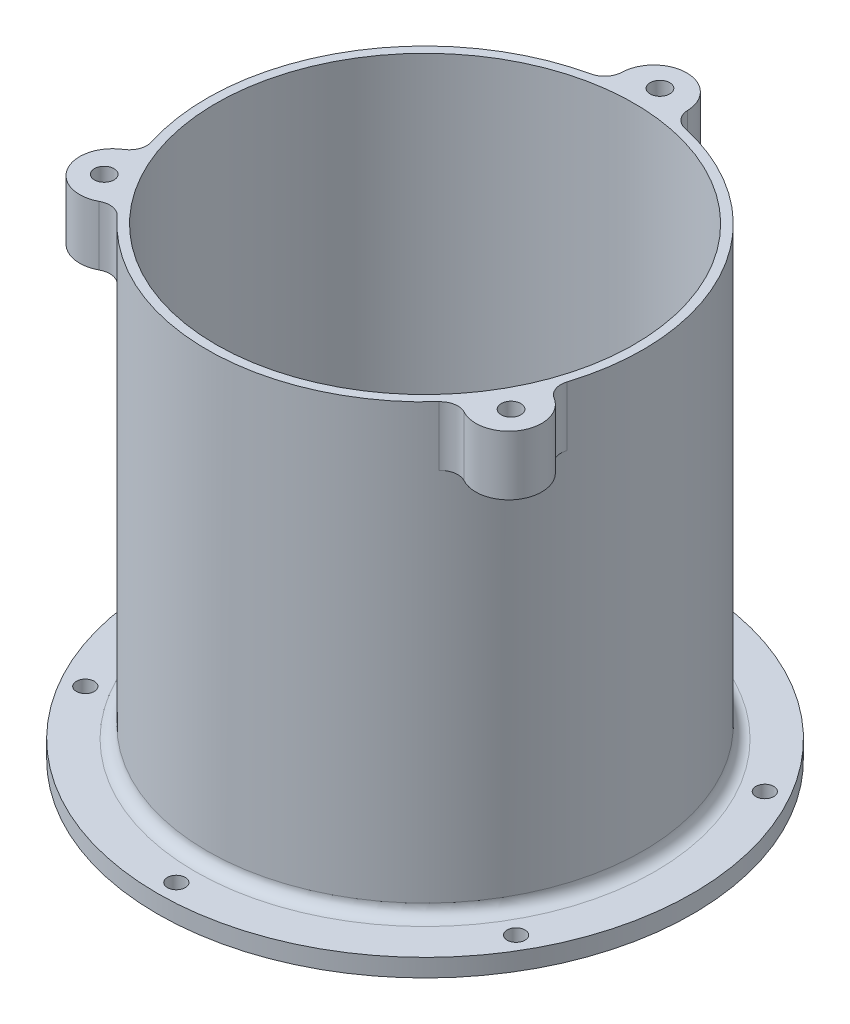
SolidWorks part; units mm, degrees
ref_plane "Front Plane" through (0, 0, 0) normal (0, 0, 1) x (1, 0, 0)
ref_plane "Top Plane" through (0, 0, 0) normal (0, 1, 0) x (1, 0, 0)
ref_plane "Right Plane" through (0, 0, 0) normal (1, 0, 0) x (0, 0, -1)
sketch "Sketch3" plane through (0, 0, 0) normal (0, 1, 0) x (1, 0, 0)
  circle A0 centre (0, 0) radius 45
  circle A1 centre (0, 0) radius 35.15
  dimension "D1" = 70.3
  dimension "D2" = 90
extrude "Boss-Extrude4" add sketch "Sketch3" along normal blind 3
sketch "Sketch4" plane through (0, 3, 0) normal (0, 1, 0) x (1, 0, 0)
  circle A1 centre (0, 0) radius 35.15
  circle A2 centre (0, 0) radius 36.65
  dimension "D1" = 70.3
  dimension "D2" = 73.3
extrude "Boss-Extrude5" add sketch "Sketch4" along normal blind 75
fillet "Fillet1" radius 2 1 edges at (0, 3, 36.65)
sketch "Sketch7" plane through (0, 3, 0) normal (0, 1, 0) x (1, 0, 0)
  line L0 (0, 0) -> (0, 41.825) construction
  circle A1 centre (0, 41.825) radius 1.5
  circle A2 centre (36.2215, 20.9125) radius 1.5
  circle A3 centre (36.2215, -20.9125) radius 1.5
  circle A4 centre (0, -41.825) radius 1.5
  circle A5 centre (-36.2215, -20.9125) radius 1.5
  circle A6 centre (-36.2215, 20.9125) radius 1.5
  point P18 (0, 0)
  dimension "D1" = 41.825
  dimension "D2" = 6
extrude "Cut-Extrude2" cut sketch "Sketch7" against normal through all
sketch "Sketch8" plane through (0, 78, 0) normal (0, 1, 0) x (1, 0, 0)
  line L0 (0, 0) -> (0, 44) construction
  line L1 (0, 0) -> (5.1007, 36.2933) construction
  line L2 (0, 0) -> (-5.1007, 36.2933) construction
  circle A0 centre (0, 0) radius 36.65 construction
  arc A1 (-5.1007, 36.2933) -> (5.1007, 36.2933) centre (0, 0) cw
  arc A3 (33.9813, -13.7293) -> (28.8806, -22.564) centre (31.943, -18.4423) cw
  arc A4 (-28.8806, -22.564) -> (-33.9813, -13.7293) centre (-31.943, -18.4423) cw
  arc A5 (-5.1007, 36.2933) -> (5.1007, 36.2933) centre (0, 38.4638) cw
  arc A6 (33.9813, -13.7293) -> (28.8806, -22.564) centre (33.3107, -19.2319) cw
  arc A7 (33.9813, -13.7293) -> (28.8806, -22.564) centre (0, 0) cw
  arc A8 (-5.1007, 36.2933) -> (5.1007, 36.2933) centre (0, 36.8846) cw
  arc A9 (-28.8806, -22.564) -> (-33.9813, -13.7293) centre (-31.943, -18.4423) cw
  arc A10 (-28.8806, -22.564) -> (-33.9813, -13.7293) centre (-33.3107, -19.2319) cw
  arc A11 (-28.8806, -22.564) -> (-33.9813, -13.7293) centre (0, 0) cw
  arc A12 (33.9813, -13.7293) -> (28.8806, -22.564) centre (31.943, -18.4423) cw
  arc A13 (-5.1007, 36.2933) -> (5.1007, 36.2933) centre (0, 36.8846) cw
  point P19 (0, 0)
  point P37 (0, 0)
  dimension "D1" = 8
  dimension "D2" = 8
  dimension "D3" = 3
extrude "Boss-Extrude7" add sketch "Sketch8" against normal blind 10
sketch "Sketch9" plane through (0, 78, 0) normal (0, 1, 0) x (1, 0, 0)
  line L0 (0, 0) -> (0, 39.5) construction
  circle A0 centre (0, 39.5) radius 1.65
  circle A1 centre (34.208, -19.75) radius 1.65
  circle A2 centre (-34.208, -19.75) radius 1.65
  point P11 (0, 0)
  dimension "D1" = 3.3
  dimension "D3" = 39.5
  dimension "D2" = 3
extrude "Cut-Extrude3" cut sketch "Sketch9" against normal blind 10
fillet "Fillet2" radius 3 6 edges at (5.1007, 73, -36.2933) (-5.1007, 73, -36.2933) (28.8806, 73, 22.564) (33.9813, 73, 13.7293) (-33.9813, 73, 13.7293) (-28.8806, 73, 22.564)
